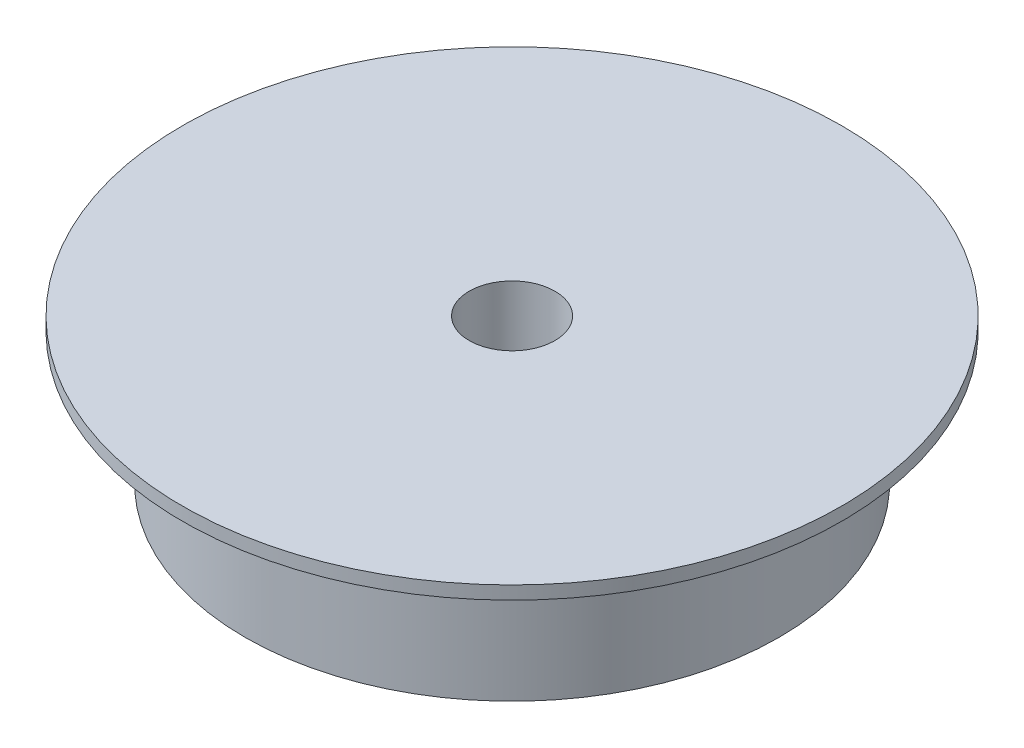
SolidWorks part; units mm, degrees
ref_plane "Front Plane" through (0, 0, 0) normal (0, 0, 1) x (1, 0, 0)
ref_plane "Top Plane" through (0, 0, 0) normal (0, 1, 0) x (1, 0, 0)
ref_plane "Right Plane" through (0, 0, 0) normal (1, 0, 0) x (0, 0, -1)
sketch "Sketch1" plane through (0, 0, 0) normal (0, 0, 1) x (1, 0, 0)
  line L0 (0, 0) -> (0, 62.0728) construction
  line L1 (16.25, 0) -> (16.25, 55)
  line L2 (16.25, 55) -> (125, 55)
  line L3 (125, 55) -> (125, 50)
  line L4 (125, 50) -> (101.25, 50)
  line L5 (101.25, 50) -> (101.25, 0)
  line L6 (101.25, 0) -> (16.25, 0)
  dimension "D1" = 32.5
  dimension "D2" = 125
  dimension "D3" = 5
  dimension "D4" = 50
  dimension "D5" = 85
revolve "Revolve1" add sketch "Sketch1" angle 360 about L0
